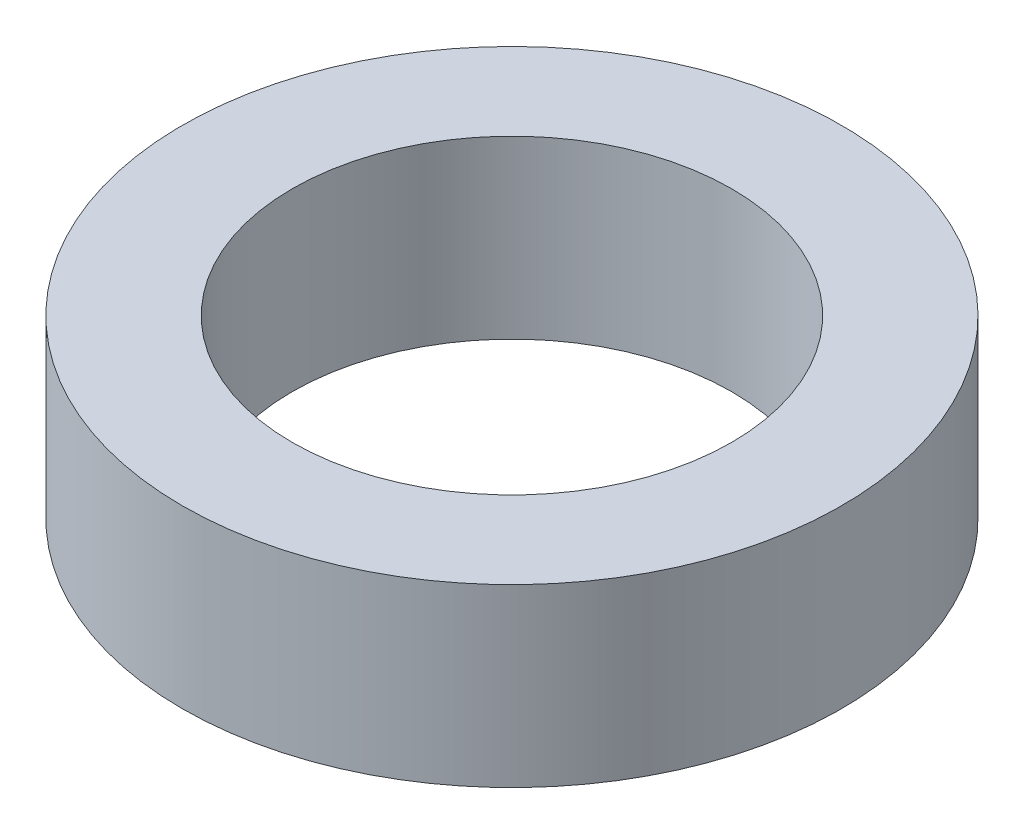
SolidWorks part; units mm, degrees
ref_plane "Front" through (0, 0, 0) normal (0, 0, 1) x (1, 0, 0)
ref_plane "Top" through (0, 0, 0) normal (0, 1, 0) x (1, 0, 0)
ref_plane "Right" through (0, 0, 0) normal (1, 0, 0) x (0, 0, -1)
sketch "Sketch1" plane through (0, 0, 0) normal (0, 1, 0) x (1, 0, 0)
  circle A0 centre (0, 0) radius 5
  circle A1 centre (0, 0) radius 7.5
  dimension "D1" = 10
  dimension "D2" = 15
extrude "Boss-Extrude1" add sketch "Sketch1" along normal blind 4
